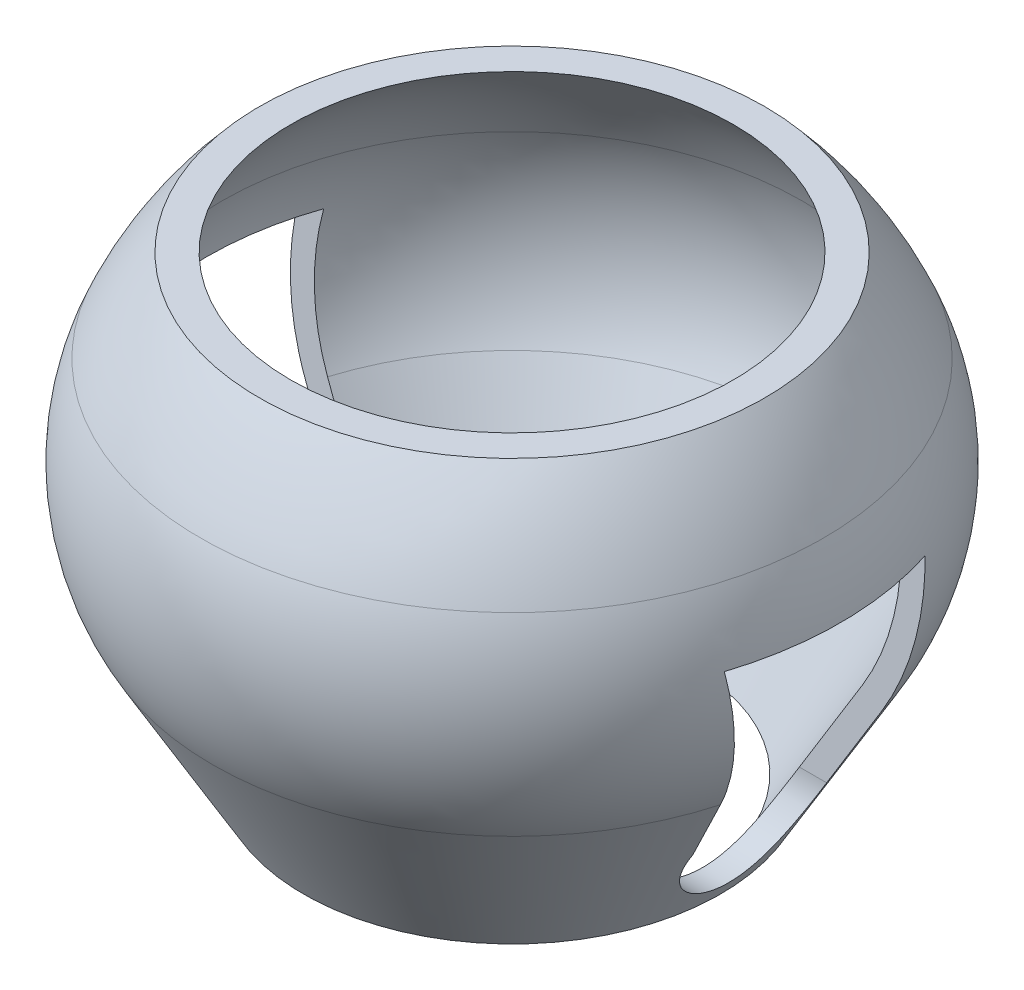
SolidWorks part; units mm, degrees
ref_plane "Front Plane" through (0, 0, 0) normal (0, 0, 1) x (1, 0, 0)
ref_plane "Top Plane" through (0, 0, 0) normal (0, 1, 0) x (1, 0, 0)
ref_plane "Right Plane" through (0, 0, 0) normal (1, 0, 0) x (0, 0, -1)
sketch "Sketch5" plane through (0, 0, 0) normal (0, 1, 0) x (1, 0, 0)
  line L0 (0, 0) -> (-15, 0) construction
  line L1 (-15, 0) -> (0, 0)
  arc A0 (-15, 0) -> (0, 0) centre (-7.5, 0) ccw
  dimension "D1" = 15
revolve "Revolve1" add sketch "Sketch5" angle 180 about L0
sketch "Sketch8" plane through (0, 0, 0) normal (0, -1, 0) x (1, 0, 0)
  circle A1 centre (-7.5, 0) radius 7.5
  circle A2 centre (-7.5, 0) radius 7.5
  dimension "D1" = 0
extrude "Boss-Extrude1" add sketch "Sketch8" along normal blind 5 draft 30
fillet "Fillet3" radius 5 1 edges at (-7.5, 0, -7.5)
shell "Shell7" thickness 0.5
sketch "Sketch9" plane through (0, 0, 0) normal (1, 0, 0) x (0, 0, -1)
  line L0 (0, 2.9627) -> (0, -5) construction
  line L1 (1.5573, -3.2457) -> (2.2201, 1.5297)
  line L2 (6.89, 2.9627) -> (-6.89, 2.9627) construction
  line L3 (-4.6132, -5) -> (4.6132, -5) construction
  line L4 (-2.2201, 1.5297) -> (2.2201, 1.5297)
  line L5 (-1.5561, -2.995) -> (-2.2201, 1.5297)
  arc A2 (-1.5561, -2.995) -> (1.5573, -3.2457) centre (0, -3.128) ccw
extrude "Cut-Extrude1" cut sketch "Sketch9" against normal blind 23
ref_plane "Plane1" through (0, 7.5, 0) normal (0, 1, 0) x (1, 0, 0)
sketch "Sketch11" plane through (0, 7.5, 0) normal (0, 1, 0) x (1, 0, 0)
  line L0 (-7.5, 6.89) -> (-0.61, 6.89)
  line L1 (-0.61, 6.89) -> (-0.61, -6.89)
  line L2 (-14.7672, 0) -> (-14.7672, -6.89)
  line L3 (-14.7672, 0) -> (-14.7672, 6.89)
  line L4 (-14.7672, 6.89) -> (-7.5, 6.89)
  line L5 (-14.7672, -6.89) -> (-0.61, -6.89)
  circle A1 centre (-7.5, 0) radius 6.89 construction
  arc A2 (-14.4198, 2.2201) -> (-14.4198, -2.2201) centre (-7.5, 0) ccw construction
extrude "Cut-Extrude4" cut sketch "Sketch11" against normal blind 2.5
ref_plane "Plane2" through (0, 0, 7.3) normal (0, 0, 1) x (1, 0, 0)
sketch "Sketch13" plane through (0, 0, 7.3) normal (0, 0, 1) x (1, 0, 0)
  line L0 (-2.8197, -2.4128) -> (-3.4195, 2.0902)
  line L1 (-7.5, 5) -> (-7.5, -5) construction
  line L2 (-11.5805, 2.0902) -> (-3.4195, 2.0902)
  line L4 (-1.9098, 5) -> (-13.0902, 5) construction
  line L5 (-12.1132, -5) -> (-2.8868, -5) construction
  line L6 (-12.1803, -2.4128) -> (-11.5805, 2.0902)
  line L7 (-12.1803, -2.4128) -> (-9.9609, -5.5838)
  line L9 (-2.8197, -2.4128) -> (-5.0391, -5.5838)
  line L11 (-9.9609, -5.5838) -> (-5.0391, -5.5838)
  point P14 (-7.5, 2.0902)
